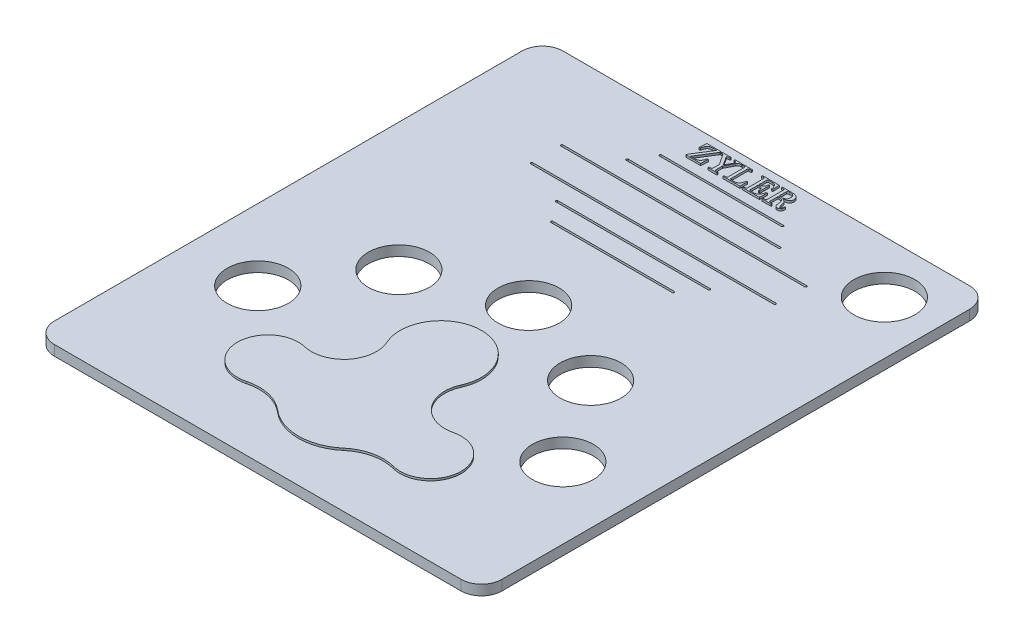
SolidWorks part; units mm, degrees
material "Epoxy, Unfilled"
ref_plane "Front Plane" through (0, 0, 0) normal (0, 0, 1) x (1, 0, 0)
ref_plane "Top Plane" through (0, 0, 0) normal (0, 1, 0) x (1, 0, 0)
ref_plane "Right Plane" through (0, 0, 0) normal (1, 0, 0) x (0, 0, -1)
sketch "Sketch1" plane through (0, 0, 0) normal (0, 1, 0) x (1, 0, 0)
  line L1 (-110, -125) -> (110, -125)
  line L2 (-110, -125) -> (-110, 125)
  line L3 (-110, 125) -> (110, 125)
  line L4 (110, -125) -> (110, 125)
  line L5 (-110, -125) -> (110, 125) construction
  line L6 (-110, 125) -> (110, -125) construction
  point P0 (0, 0)
  dimension "D1" = 220
  dimension "D2" = 250
extrude "Boss-Extrude1" add sketch "Sketch1" along normal blind 5
sketch "Sketch2" plane through (0, 5, 0) normal (0, 1, 0) x (1, 0, 0)
  line L0 (37.0834, 94.5) -> (-37.9166, 94.5) construction
  line L1 (37.0834, 94) -> (-37.9166, 94)
  line L2 (37.0834, 95) -> (-37.9166, 95)
  line L3 (59.9726, 84.5076) -> (-60.0274, 84.5076) construction
  line L4 (59.9726, 84.0076) -> (-60.0274, 84.0076)
  line L5 (59.9726, 85.0076) -> (-60.0274, 85.0076)
  line L6 (59.7247, 69.5076) -> (-59.7753, 69.5076) construction
  line L7 (59.7247, 69.0076) -> (-59.7753, 69.0076)
  line L8 (59.7247, 70.0076) -> (-59.7753, 70.0076)
  line L9 (37.4747, 59.5076) -> (-37.5253, 59.5076) construction
  line L10 (37.4747, 59.0076) -> (-37.5253, 59.0076)
  line L11 (37.4747, 60.0076) -> (-37.5253, 60.0076)
  line L12 (110, 125) -> (-110, 125) construction
  line L13 (28.5009, 104.5) -> (-31.4991, 104.5) construction
  line L14 (28.5009, 104) -> (-31.4991, 104)
  line L15 (28.5009, 105) -> (-31.4991, 105)
  line L16 (29.8122, 49.5076) -> (-29.8627, 49.5076) construction
  line L17 (29.8122, 49.0076) -> (-29.8627, 49.0076)
  line L18 (29.8122, 50.0076) -> (-29.8627, 50.0076)
  arc A0 (37.0834, 94) -> (37.0834, 95) centre (37.0834, 94.5) ccw
  arc A1 (-37.9166, 95) -> (-37.9166, 94) centre (-37.9166, 94.5) ccw
  arc A2 (59.9726, 84.0076) -> (59.9726, 85.0076) centre (59.9726, 84.5076) ccw
  arc A3 (-60.0274, 85.0076) -> (-60.0274, 84.0076) centre (-60.0274, 84.5076) ccw
  arc A4 (59.7247, 69.0076) -> (59.7247, 70.0076) centre (59.7247, 69.5076) ccw
  arc A5 (-59.7753, 70.0076) -> (-59.7753, 69.0076) centre (-59.7753, 69.5076) ccw
  arc A6 (37.4747, 59.0076) -> (37.4747, 60.0076) centre (37.4747, 59.5076) ccw
  arc A7 (-37.5253, 60.0076) -> (-37.5253, 59.0076) centre (-37.5253, 59.5076) ccw
  arc A8 (28.5009, 104) -> (28.5009, 105) centre (28.5009, 104.5) ccw
  arc A9 (-31.4991, 105) -> (-31.4991, 104) centre (-31.4991, 104.5) ccw
  arc A10 (29.8122, 49.0076) -> (29.8122, 50.0076) centre (29.8122, 49.5076) ccw
  arc A11 (-29.8627, 50.0076) -> (-29.8627, 49.0076) centre (-29.8627, 49.5076) ccw
  point P2 (-0.4166, 94.5)
  point P8 (-0.0274, 84.5076)
  point P15 (-0.0253, 69.5076)
  point P22 (-0.0253, 59.5076)
  point P30 (-60.2753, 69.5076)
  point P33 (-1.4991, 104.5)
  point P40 (-0.0253, 49.5076)
  dimension "D5" = 0.5
  dimension "D6" = 0.5
  dimension "D8" = 0.5
  dimension "D9" = 0.5
  dimension "D16" = 0.5
  dimension "D17" = 0.5
  dimension "D1" = 30
  dimension "D2" = 10
  dimension "D3" = 15
  dimension "D4" = 10
  dimension "D7" = 120
  dimension "D10" = 60
  dimension "D11" = 75
  dimension "D12" = 120
  dimension "D13" = 75
  dimension "D14" = 10
  dimension "D15" = 10
extrude "Cut-Extrude1" cut sketch "Sketch2" against normal blind 20
sketch "Sketch3" plane through (0, 5, 0) normal (0, 1, 0) x (1, 0, 0)
  line L0 (-110, -125) -> (110, -125) construction
  line L1 (-110, 125) -> (-110, -125) construction
  line L2 (110, -125) -> (110, 125) construction
  circle A0 centre (-75, -50) radius 15
  circle A1 centre (-47.1428, -8.4792) radius 15
  circle A2 centre (0, 8.1808) radius 15
  circle A3 centre (75, -50) radius 15
  circle A4 centre (47.1428, -8.4792) radius 15
  dimension "D1" = 30
  dimension "D2" = 75
  dimension "D3" = 35
  dimension "D4" = 50
  dimension "D5" = 50
  dimension "D6" = 50
  dimension "D7" = 50
  dimension "D8" = 35
  dimension "D9" = 116.5208
extrude "Cut-Extrude2" cut sketch "Sketch3" against normal blind 20
sketch "Sketch4" plane through (0, 5, 0) normal (0, 1, 0) x (1, 0, 0)
  line L0 (110, 125) -> (-110, 125) construction
  line L2 (-110, -125) -> (110, -125) construction
  arc A0 (18.2194, -43.2494) -> (-18.2194, -43.2494) centre (0, -35) ccw
  arc A1 (-16.2234, -99.0211) -> (16.2234, -99.0211) centre (0, -80) ccw
  arc A2 (-36.5137, -65.4108) -> (-36.1486, -94.4971) centre (-40, -80) ccw
  arc A3 (36.1486, -94.4971) -> (36.5137, -65.4108) centre (40, -80) ccw
  arc A4 (18.2194, -43.2494) -> (36.5137, -65.4108) centre (32.795, -49.8489) ccw
  arc A5 (-36.5137, -65.4108) -> (-18.2194, -43.2494) centre (-32.795, -49.8489) ccw
  arc A6 (-16.2234, -99.0211) -> (-36.1486, -94.4971) centre (-30.5, -115.7596) ccw
  arc A7 (36.1486, -94.4971) -> (16.2234, -99.0211) centre (30.5, -115.7596) ccw
  point P20 (0, 125)
  dimension "D1" = 40
  dimension "D2" = 50
  dimension "D3" = 30
  dimension "D4" = 30
  dimension "D5" = 32
  dimension "D6" = 32
  dimension "D8" = 22
  dimension "D7" = 45
extrude "Boss-Extrude2" add sketch "Sketch4" along normal blind 1
sketch "Sketch5" plane through (0, 5, 0) normal (0, 1, 0) x (1, 0, 0)
  line L0 (-110, 125) -> (-110, -125) construction
  line L1 (110, 125) -> (-110, 125) construction
  text T0 "ZYLER" font "Century Schoolbook" height 10
  dimension "D1" = 85
  dimension "D2" = 15
extrude "Boss-Extrude3" add sketch "Sketch5" along normal blind 1
fillet "Fillet1" radius 10 4 edges at (-110, 2.5, -125) (110, 2.5, -125) (110, 2.5, 125) (-110, 2.5, 125)
sketch "Sketch6" plane through (0, 5, 0) normal (0, 1, 0) x (1, 0, 0)
  circle A1 centre (83.8969, 99.1824) radius 15
  circle A3 centre (47.1428, -8.4792) radius 15 construction
  point P1 (83.8969, 99.1824)
extrude "Cut-Extrude3" cut sketch "Sketch6" against normal through all
